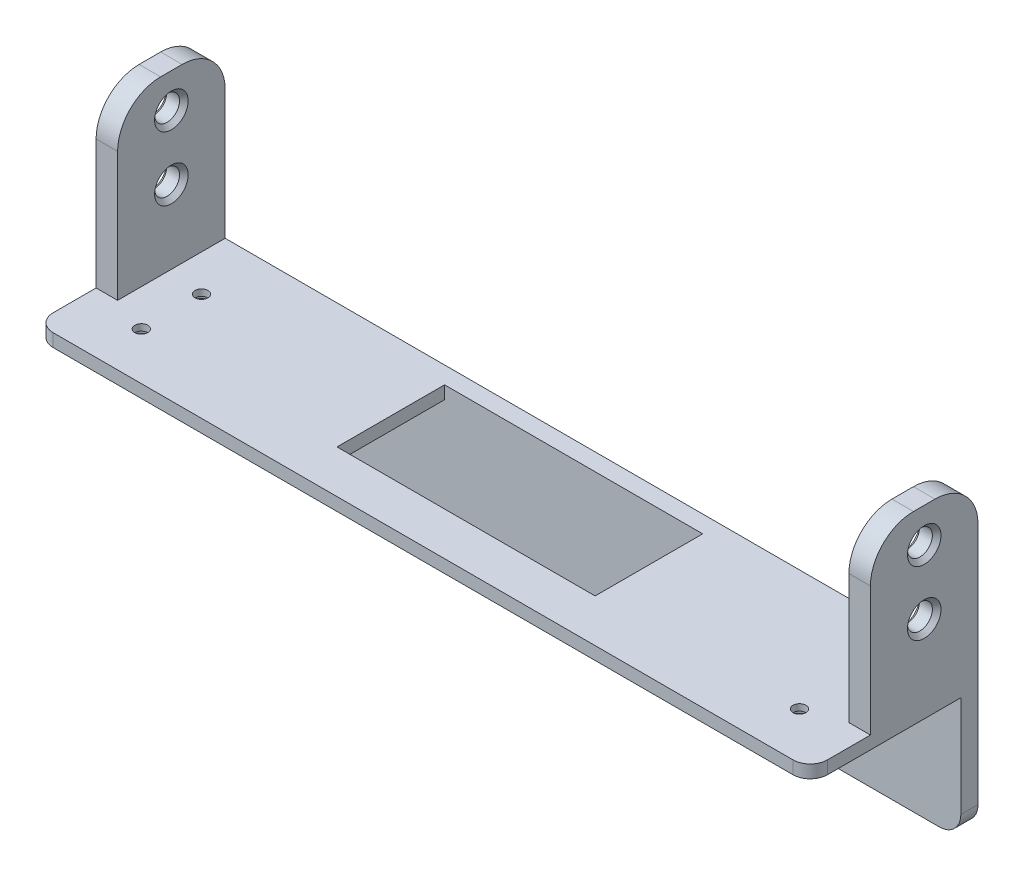
SolidWorks part; units mm, degrees
ref_plane "前视基准面" through (0, 0, 0) normal (0, 0, 1) x (1, 0, 0)
ref_plane "上视基准面" through (0, 0, 0) normal (0, 1, 0) x (1, 0, 0)
ref_plane "右视基准面" through (0, 0, 0) normal (1, 0, 0) x (0, 0, -1)
other "Configuration Table"
sketch "草图1" plane through (0, 0, 0) normal (0, 0, 1) x (1, 0, 0)
  line L1 (-90, 30) -> (90, 30)
  line L2 (-90, 30) -> (-90, -30)
  line L3 (-90, -30) -> (90, -30)
  line L4 (90, 30) -> (90, -30)
  dimension "D1" = 60
  dimension "D2" = 180
  dimension "D3" = 90
  dimension "D4" = 30
extrude "凸台-拉伸1" add sketch "草图1" along normal blind 4
sketch "草图2" plane through (0, 0, 4) normal (0, 0, 1) x (1, 0, 0)
  line L0 (-90, 30) -> (-90, -30) construction
  line L1 (-90, 1.5) -> (90, 1.5)
  line L2 (-90, 1.5) -> (-90, -1.5)
  line L3 (-90, -1.5) -> (90, -1.5)
  line L4 (90, 1.5) -> (90, -1.5)
  line L5 (90, -30) -> (90, 30) construction
  dimension "D1" = 3
  dimension "D2" = 1.5
extrude "凸台-拉伸2" add sketch "草图2" along normal blind 35
sketch "草图3" plane through (0, -1.5, 0) normal (0, -1, 0) x (1, 0, 0)
  line L0 (90, 39) -> (90, 4) construction
  line L1 (-76.5, 28) -> (76.5, 28) construction
  line L2 (-76.5, 28) -> (-76.5, 14) construction
  line L3 (-76.5, 14) -> (76.5, 14) construction
  line L4 (76.5, 28) -> (76.5, 14) construction
  line L5 (-90, 4) -> (90, 4) construction
  circle A0 centre (-76.5, 28) radius 1.5
  circle A1 centre (-76.5, 14) radius 1.5
  circle A2 centre (76.5, 28) radius 1.5
  circle A3 centre (76.5, 14) radius 1.5
  dimension "D5" = 3
  dimension "D1" = 14
  dimension "D2" = 153
  dimension "D3" = 13.5
  dimension "D4" = 10
extrude "切除-拉伸1" cut sketch "草图3" against normal blind 50
fillet "圆角3" radius 4 2 edges at (-90, 0, 39) (90, 0, 39)
sketch "草图6" plane through (0, -1.5, 0) normal (0, -1, 0) x (1, 0, 0)
  circle A0 centre (-76.5, 28) radius 3
  circle A1 centre (-76.5, 14) radius 3
  circle A2 centre (76.5, 28) radius 3
  circle A3 centre (76.5, 14) radius 3
  dimension "D1" = 6
extrude "切除-拉伸4" cut sketch "草图6" against normal blind 1.5
sketch "草图7" plane through (0, 1.5, 0) normal (0, 1, 0) x (1, 0, 0)
  line L0 (90, -4) -> (-90, -4) construction
  line L1 (-30, -4) -> (30, -4)
  line L2 (-30, -4) -> (-30, -29)
  line L3 (-30, -29) -> (30, -29)
  line L4 (30, -4) -> (30, -29)
  dimension "D1" = 60
  dimension "D2" = 30
  dimension "D3" = 25
extrude "切除-拉伸5" cut sketch "草图7" against normal blind 10
sketch "草图8" plane through (0, 0, 4) normal (0, 0, 1) x (1, 0, 0)
  line L1 (-90, 1.5) -> (90, 1.5)
  line L2 (-90, 1.5) -> (-90, 30)
  line L3 (-90, 30) -> (90, 30)
  line L4 (90, 1.5) -> (90, 30)
extrude "切除-拉伸6" cut sketch "草图8" against normal through all both and the other way through all
sketch "草图9" plane through (90, 0, 0) normal (1, 0, 0) x (0, 0, -1)
  line L1 (0, 1.5) -> (-25, 1.5)
  line L2 (0, 1.5) -> (0, 41.5)
  line L3 (0, 41.5) -> (-25, 41.5)
  line L4 (-25, 1.5) -> (-25, 41.5)
  dimension "D1" = 40
  dimension "D2" = 25
extrude "凸台-拉伸3" add sketch "草图9" against normal blind 5
mirror "镜向1" about plane through (0, 0, 0) normal (1, 0, 0) of "凸台-拉伸3"
sketch "草图10" plane through (90, 0, 0) normal (1, 0, 0) x (0, 0, -1)
  line L0 (0, -30) -> (0, 41.5) construction
  line L1 (0, 41.5) -> (-25, 41.5) construction
  circle A0 centre (-12.5, 33.5) radius 2.9
  circle A1 centre (-12.5, 18.6) radius 2.9
  point P8 (0, 0)
  dimension "D1" = 5.8
  dimension "D4" = 14.9
  dimension "D5" = 5.8
  dimension "D2" = 12.5
  dimension "D3" = 8
extrude "切除-拉伸7" cut sketch "草图10" against normal through all both and the other way through all
chamfer "倒角2" distance 1 angle 45 4 edges at (85, 36.4, 12.5) (90, 30.6, 12.5) (-85, 30.6, 12.5) (-90, 36.4, 12.5)
fillet "圆角4" radius 5 2 edges at (-90, -30, 2) (90, -30, 2)
chamfer "倒角3" distance 1 angle 45 2 edges at (-90, 21.5, 12.5) (90, 15.7, 12.5)
fillet "圆角5" radius 10 4 edges at (87.5, 41.5, 0) (87.5, 41.5, 25) (-87.5, 41.5, 0) (-87.5, 41.5, 25)
chamfer "倒角4" distance 1 angle 45 2 edges at (85, 21.5, 12.5) (-85, 15.7, 12.5)
